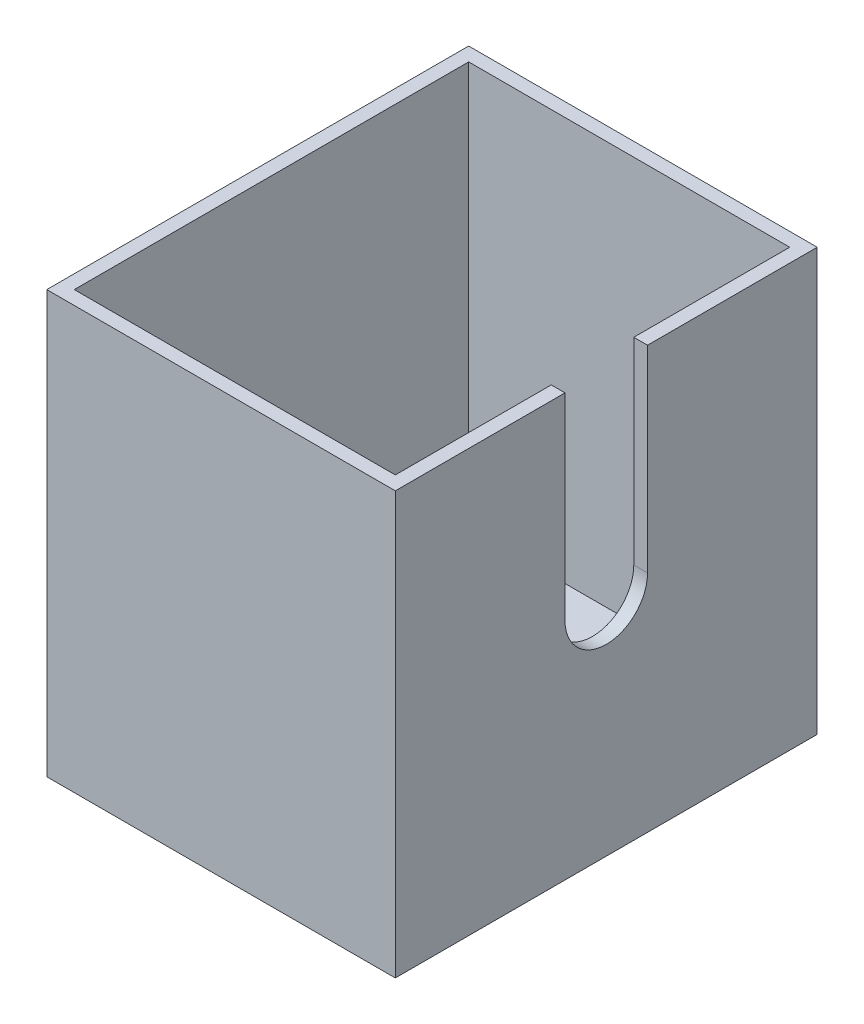
SolidWorks part; units mm, degrees
other "Marquage1"
sketch "Esquisse7" plane through (-22.1, 26.1, 52.2) normal (-0.1348, 0.2678, 0.954) x (-0.088, -0.9622, 0.2577)
ref_plane "Plan de face" through (0, 0, 0) normal (0, 0, 1) x (1, 0, 0)
ref_plane "Plan de dessus" through (0, 0, 0) normal (0, 1, 0) x (1, 0, 0)
ref_plane "Plan de droite" through (0, 0, 0) normal (1, 0, 0) x (0, 0, -1)
sketch "Esquisse1" plane through (0, 0, 0) normal (0, 0, 1) x (1, 0, 0)
  line L1 (-22.1, 26.1) -> (22.1, 26.1)
  line L2 (-22.1, 26.1) -> (-22.1, -26.1)
  line L3 (-22.1, -26.1) -> (22.1, -26.1)
  line L4 (22.1, 26.1) -> (22.1, -26.1)
  line L5 (-22.1, 26.1) -> (22.1, -26.1) construction
  line L6 (-22.1, -26.1) -> (22.1, 26.1) construction
  point P0 (0, 0)
  dimension "D1" = 44.2
  dimension "D2" = 52.2
extrude "Boss.-Extru.1" add sketch "Esquisse1" along normal blind 52.2
sketch "Esquisse2" plane through (22.1, 0, 0) normal (1, 0, 0) x (0, 0, -1)
  line L0 (-52.2, -19.9) -> (-28.55, -19.9)
  line L1 (-52.2, -26.1) -> (-52.2, 26.1) construction
  line L2 (-28.55, -19.9) -> (-28.55, -21.45)
  line L3 (-28.55, -21.45) -> (-32.25, -21.45)
  line L4 (-32.25, -21.45) -> (-32.25, -22.45)
  line L5 (-32.25, -22.45) -> (-28.7456, -26.1)
  line L6 (-52.2, -26.1) -> (0, -26.1) construction
  dimension "D1" = 23.65
  dimension "D2" = 6.2
  dimension "D3" = 1.55
  dimension "D4" = 3.7
  dimension "D5" = 1
  dimension "D6" = 5.06
extrude "Enlèv. mat.-Extru.2" cut sketch "Esquisse2" against normal blind 44.2 and the other way through all flip side to cut
sketch "Esquisse3" plane through (22.1, 0, 0) normal (1, 0, 0) x (0, 0, -1)
  line L0 (0, -19.9) -> (-23.65, -19.9)
  line L1 (0, -26.1) -> (0, 26.1) construction
  line L2 (-23.65, -19.9) -> (-23.65, -21.45)
  line L3 (-23.65, -21.45) -> (-19.95, -21.45)
  line L4 (-19.95, -21.45) -> (-19.95, -22.45)
  line L5 (-19.95, -22.45) -> (-23.4544, -26.1)
  line L6 (-28.7456, -26.1) -> (0, -26.1) construction
  dimension "D1" = 6.2
  dimension "D2" = 23.65
  dimension "D3" = 1.55
  dimension "D4" = 3.7
  dimension "D5" = 1
  dimension "D6" = 5.06
extrude "Enlèv. mat.-Extru.3" cut sketch "Esquisse3" against normal blind 44.2 and the other way through all
sketch "Esquisse4" plane through (0, 26.1, 0) normal (0, 1, 0) x (1, 0, 0)
  line L0 (-15.9, -52.2) -> (-15.9, -28.55)
  line L1 (22.1, -52.2) -> (-22.1, -52.2) construction
  line L2 (-15.9, -28.55) -> (-17.45, -28.55)
  line L3 (-17.45, -28.55) -> (-17.45, -32.25)
  line L4 (-17.45, -32.25) -> (-18.45, -32.25)
  line L5 (-18.45, -32.25) -> (-22.1, -28.7456)
  line L6 (-22.1, -52.2) -> (-22.1, 0) construction
  dimension "D1" = 6.2
  dimension "D2" = 23.65
  dimension "D3" = 1.55
  dimension "D4" = 3.7
  dimension "D5" = 1
  dimension "D6" = 5.06
extrude "Enlèv. mat.-Extru.4" cut sketch "Esquisse4" against normal blind 46 and the other way through all
sketch "Esquisse5" plane through (0, 26.1, 0) normal (0, 1, 0) x (1, 0, 0)
  line L0 (-15.9, 0) -> (-15.9, -23.65)
  line L1 (22.1, 0) -> (-22.1, 0) construction
  line L2 (-15.9, -23.65) -> (-17.45, -23.65)
  line L3 (-17.45, -23.65) -> (-17.45, -19.95)
  line L4 (-17.45, -19.95) -> (-18.45, -19.95)
  line L5 (-18.45, -19.95) -> (-22.1, -23.4544)
  line L6 (-22.1, -28.7456) -> (-22.1, 0) construction
  dimension "D1" = 6.2
  dimension "D2" = 23.65
  dimension "D3" = 1.55
  dimension "D4" = 3.7
  dimension "D5" = 1
  dimension "D6" = 5.06
extrude "Enlèv. mat.-Extru.5" cut sketch "Esquisse5" against normal blind 46 and the other way through all flip side to cut
sketch "Esquisse6" plane through (0, 0, 28.55) normal (0, 0, 1) x (1, 0, 0)
  line L0 (-22.1, -19.9) -> (-15.9, -19.9)
  line L1 (-15.9, -19.9) -> (-15.9, -26.0936)
extrude "Enlèv. mat.-Extru.7" cut sketch "Esquisse6" against normal through all both and the other way through all flip side to cut
sketch "Esquisse11" plane through (0, 26.1, 0) normal (0, 1, 0) x (1, 0, 0)
  line L0 (22.1, -52.2) -> (22.1, 0) construction
  line L1 (22.1, -49.1) -> (-15.9, -49.1)
  line L2 (-15.9, -28.55) -> (-15.9, -52.2) construction
  line L3 (22.1, -52.2) -> (-15.9, -52.2) construction
  dimension "D1" = 3.1
extrude "Enlèv. mat.-Extru.8" cut sketch "Esquisse11" against normal blind 46 and the other way through all
sketch "Esquisse12" plane through (0, 26.1, 0) normal (0, 1, 0) x (1, 0, 0)
  line L0 (22.1, -49.1) -> (22.1, 0) construction
  line L1 (22.1, -3.1) -> (-15.9, -3.1)
  line L2 (-15.9, -23.65) -> (-15.9, 0) construction
  line L3 (22.1, 0) -> (-15.9, 0) construction
  dimension "D1" = 3.1
extrude "Enlèv. mat.-Extru.9" cut sketch "Esquisse12" against normal blind 46 and the other way through all flip side to cut
sketch "Esquisse13" plane through (0, 26.1, 0) normal (0, 1, 0) x (1, 0, 0)
  line L0 (-14.4, -4.6) -> (-14.4, -47.6)
  line L1 (-14.4, -47.6) -> (20.6, -47.6)
  line L2 (20.6, -47.6) -> (20.6, -4.6)
  line L3 (20.6, -4.6) -> (-14.4, -4.6)
  line L5 (22.1, -49.1) -> (22.1, -3.1) construction
  line L6 (-15.9, -23.65) -> (-15.9, -3.1) construction
  line L7 (-15.9, -3.1) -> (22.1, -3.1) construction
  dimension "D1" = 35
  dimension "D2" = 43
  dimension "D3" = 1.5
  dimension "D4" = 1.5
  dimension "D5" = 1.5
extrude "Enlèv. mat.-Extru.10" cut sketch "Esquisse13" against normal blind 44
sketch "Esquisse14" plane through (22.1, 0, 0) normal (1, 0, 0) x (0, 0, -1)
  line L0 (-49.1, 26.1) -> (-3.1, 26.1) construction
  line L1 (-3.1, 26.1) -> (-21.6, 26.1)
  line L2 (-21.6, 26.1) -> (-21.6, 4.6)
  line L3 (-49.1, 26.1) -> (-30.6, 26.1)
  line L4 (-30.6, 26.1) -> (-30.6, 4.6)
  arc A0 (-21.6, 4.6) -> (-30.6, 4.6) centre (-26.1, 4.6) cw
  dimension "D5" = 4.5
  dimension "D1" = 18.5
  dimension "D2" = 18.5
  dimension "D3" = 21.5
  dimension "D4" = 21.5
extrude "Enlèv. mat.-Extru.11" cut sketch "Esquisse14" against normal blind 1.5 and the other way through all
sketch "Esquisse15" plane through (22.1, 0, 0) normal (1, 0, 0) x (0, 0, -1)
  line L0 (-28.55, -19.9) -> (-23.65, -19.9)
extrude "Enlèv. mat.-Extru.13" cut sketch "Esquisse15" against normal blind 38 and the other way through all flip side to cut
sketch "Esquisse16" plane through (0, -19.9, 0) normal (0, -1, 0) x (-1, 0, 0)
  line L0 (15.9, -28.55) -> (15.9, -23.65)
extrude "Enlèv. mat.-Extru.15" cut sketch "Esquisse16" against normal blind 46 and the other way through all flip side to cut
